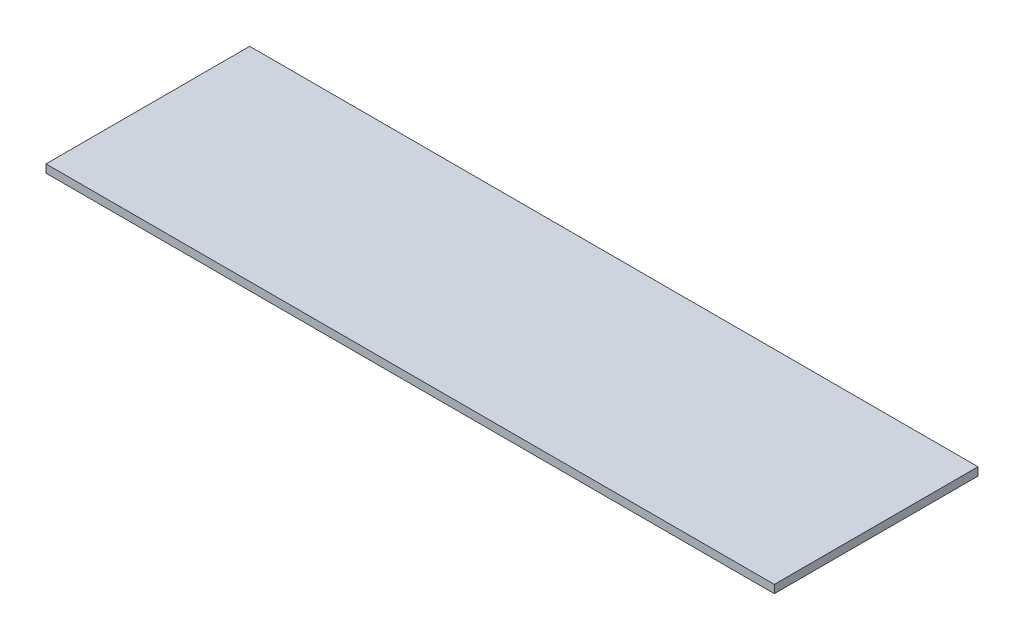
SolidWorks part; units mm, degrees
material "ABS PC"
ref_plane "Front Plane" through (0, 0, 0) normal (0, 0, 1) x (1, 0, 0)
ref_plane "Top Plane" through (0, 0, 0) normal (0, 1, 0) x (1, 0, 0)
ref_plane "Right Plane" through (0, 0, 0) normal (1, 0, 0) x (0, 0, -1)
sketch "Sketch1" plane through (0, 0, 0) normal (0, 1, 0) x (1, 0, 0)
  line L1 (-450, 125.85) -> (450, 125.85)
  line L2 (-450, 125.85) -> (-450, -125.85)
  line L3 (-450, -125.85) -> (450, -125.85)
  line L4 (450, 125.85) -> (450, -125.85)
  line L5 (-450, 125.85) -> (450, -125.85) construction
  line L6 (-450, -125.85) -> (450, 125.85) construction
  point P0 (0, 0)
  dimension "D1" = 251.7
  dimension "D2" = 900
extrude "Boss-Extrude1" add sketch "Sketch1" along normal mid plane 10
